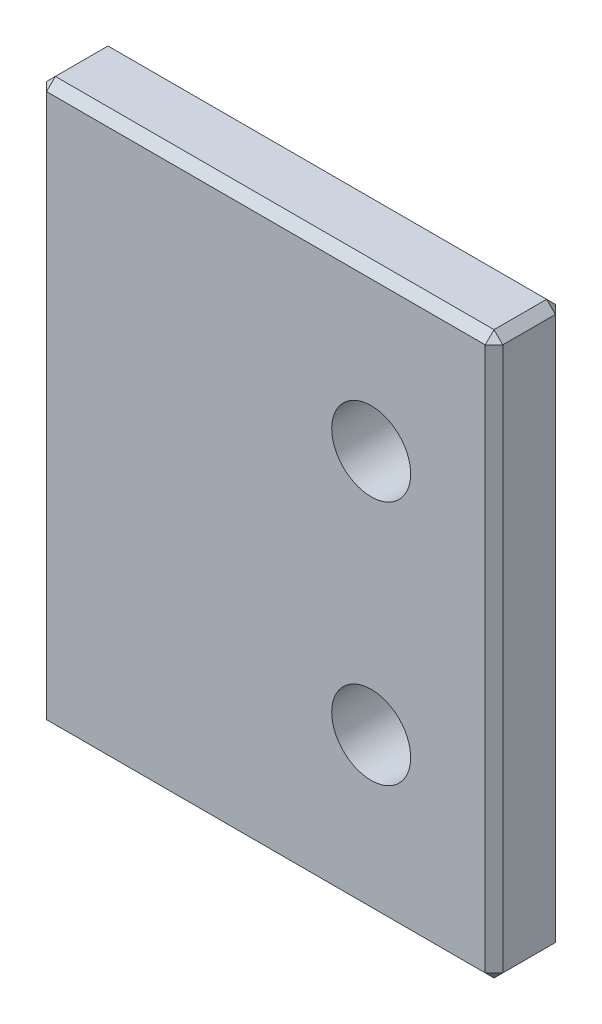
SolidWorks part; units mm, degrees
ref_plane "前视基准面" through (0, 0, 0) normal (0, 0, 1) x (1, 0, 0)
ref_plane "上视基准面" through (0, 0, 0) normal (0, 1, 0) x (1, 0, 0)
ref_plane "右视基准面" through (0, 0, 0) normal (1, 0, 0) x (0, 0, -1)
sketch "草图1" plane through (0, 0, 0) normal (0, 0, 1) x (1, 0, 0)
  line L1 (0, 0) -> (26, 0)
  line L2 (0, 0) -> (0, 32)
  line L3 (0, 32) -> (26, 32)
  line L4 (26, 0) -> (26, 32)
  dimension "D1" = 26
  dimension "D2" = 32
extrude "凸台-拉伸1" add sketch "草图1" along normal blind 4
chamfer "倒角1" distance 0.5 angle 45 12 edges at (0, 16, 4) (0, 16, 0) (0, 0, 2) (13, 0, 4) (13, 0, 0) (26, 0, 2) (26, 16, 4) (26, 16, 0) (26, 32, 2) (13, 32, 4) (0, 32, 2) (13, 32, 0)
sketch "草图2" plane through (0, 0, 0) normal (0, 0, -1) x (-1, 0, 0)
  circle A0 centre (-19, 9) radius 2.25
  circle A1 centre (-19, 23) radius 2.25
extrude "切除-拉伸1" cut sketch "草图2" against normal through all
